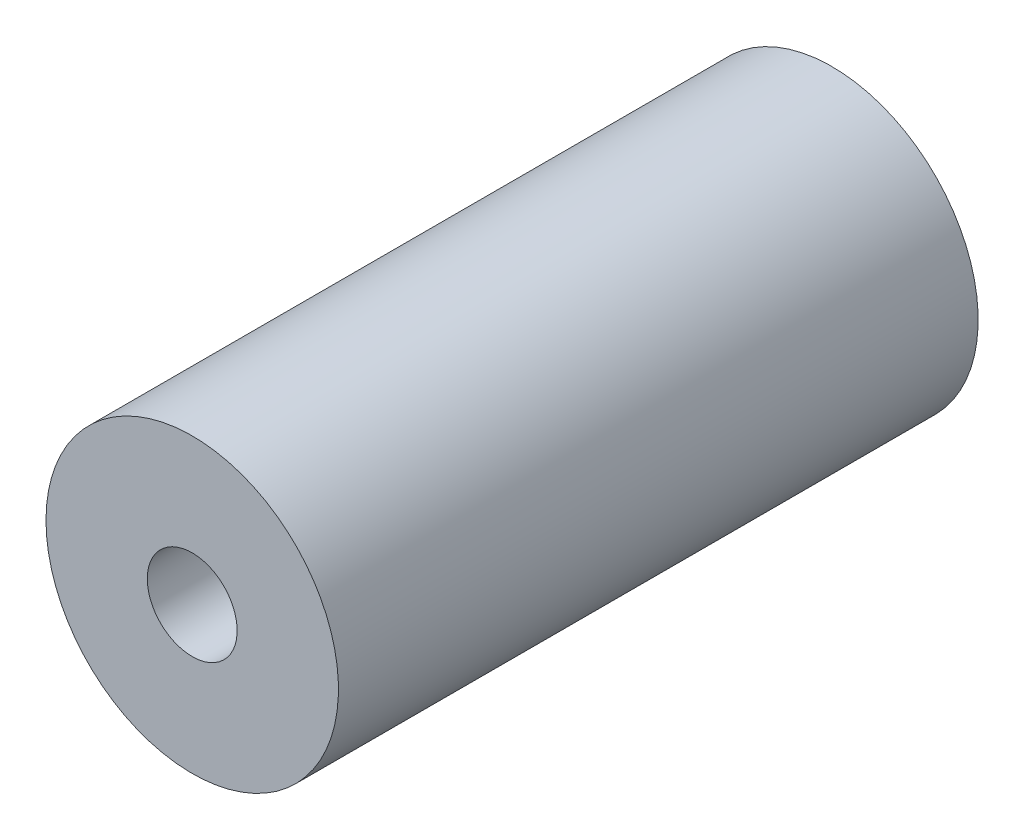
SolidWorks part; units mm, degrees
ref_plane "Front Plane" through (0, 0, 0) normal (0, 0, 1) x (1, 0, 0)
ref_plane "Top Plane" through (0, 0, 0) normal (0, 1, 0) x (1, 0, 0)
ref_plane "Right Plane" through (0, 0, 0) normal (1, 0, 0) x (0, 0, -1)
ref_plane "Plane1" through (0, 0, 0) normal (0, -1, 0) x (1, 0, 0)
sketch "Sketch1" plane through (0, 0, 0) normal (0, -1, 0) x (1, 0, 0)
  line L0 (8, 0) -> (8, 35)
  line L1 (8, 35) -> (2.4585, 35)
  line L2 (2.4585, 35) -> (2.4585, 20)
  line L3 (2.4585, 20) -> (1.75, 19.5743)
  line L4 (1.75, 19.5743) -> (1.75, 0)
  line L5 (1.75, 0) -> (8, 0)
  line L6 (0, 35) -> (0, 0) construction
revolve "Revolve1" add sketch "Sketch1" angle 360 about L6
